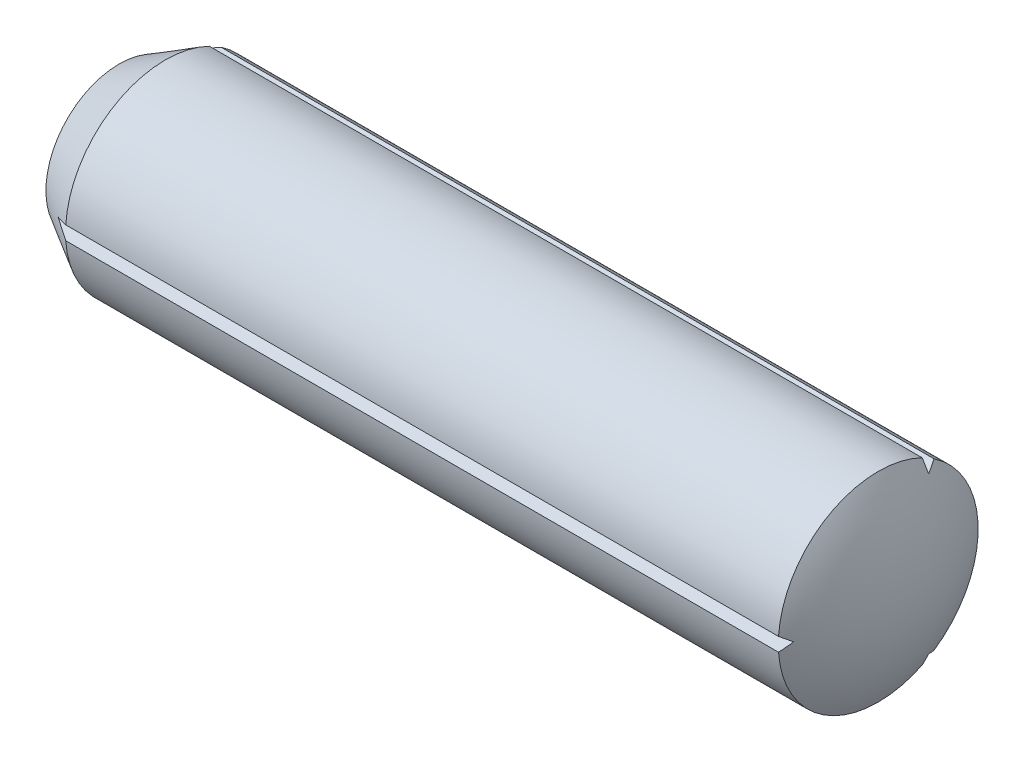
SolidWorks part; units mm, degrees
revolve "Base-Revolve" add sketch "Sketch1" angle 360 about L0
sketch "Sketch1" plane through (0, 0, 0) normal (0, 0, 1) x (1, 0, 0)
  line L0 (-117, 0) -> (21, 0) construction
  line L1 (-92.5, 12.5) -> (-98.295, 9.1543)
  line L2 (-92.5, 12.5) -> (-3.3494, 12.5)
  line L3 (-100, 0) -> (0, 0)
  line L4 (-100, 0) -> (-100, 1.25)
  arc A0 (-98.295, 9.1543) -> (-100, 1.25) centre (-75.0313, 0) ccw
  arc A1 (0, 0) -> (-3.3494, 12.5) centre (-25, 0) ccw
  dimension "D2" = 25
  dimension "D4" = 25
  dimension "Diameter" = 25
  dimension "Length" = 100
  dimension "D1" = 2.5
  dimension "D3" = 30
  dimension "Chamfer2" = 7.5
ref_plane "Plane1" through (0, 0, 0) normal (0, 0, 1) x (1, 0, 0)
ref_plane "Plane2" through (0, 0, 0) normal (0, 1, 0) x (1, 0, 0)
ref_plane "Plane3" through (0, 0, 0) normal (1, 0, 0) x (0, 0, -1)
sketch "Sketch2" plane through (0, 0, 0) normal (1, 0, 0) x (0, 0, -1)
  line L0 (0, 0) -> (-14, 0) construction
  line L1 (-11.25, 0) -> (-12.5, 0.8753)
  line L2 (-11.25, 0) -> (-12.5, -0.8753)
  line L3 (-12.5, -0.8753) -> (-12.5, 0.8753)
  circle A0 centre (0, 0) radius 11.25 construction
  circle A1 centre (0, 0) radius 12.5 construction
  dimension "D1" = 22.5
  dimension "D2" = 70
  dimension "D3" = 35
extrude "Cut-Extrude1" cut sketch "Sketch2" against normal through all
pattern_circular "CirPattern2" count 3 over 360 about axis through (0, 0, 0) along (1, 0, 0) of "Cut-Extrude1"
equation "\"D2@Sketch1\" = \"Diameter@Sketch1\""
equation "\"D1@Sketch2\" = \"Diameter@Sketch1\" * .9"
equation "\"D3@Sketch2\" = \"D2@Sketch2\" / 2"
equation "\"D1@Sketch1\" = \"Diameter@Sketch1\" * .1"
equation "\"D4@Sketch1\" = \"Diameter@Sketch1\""
